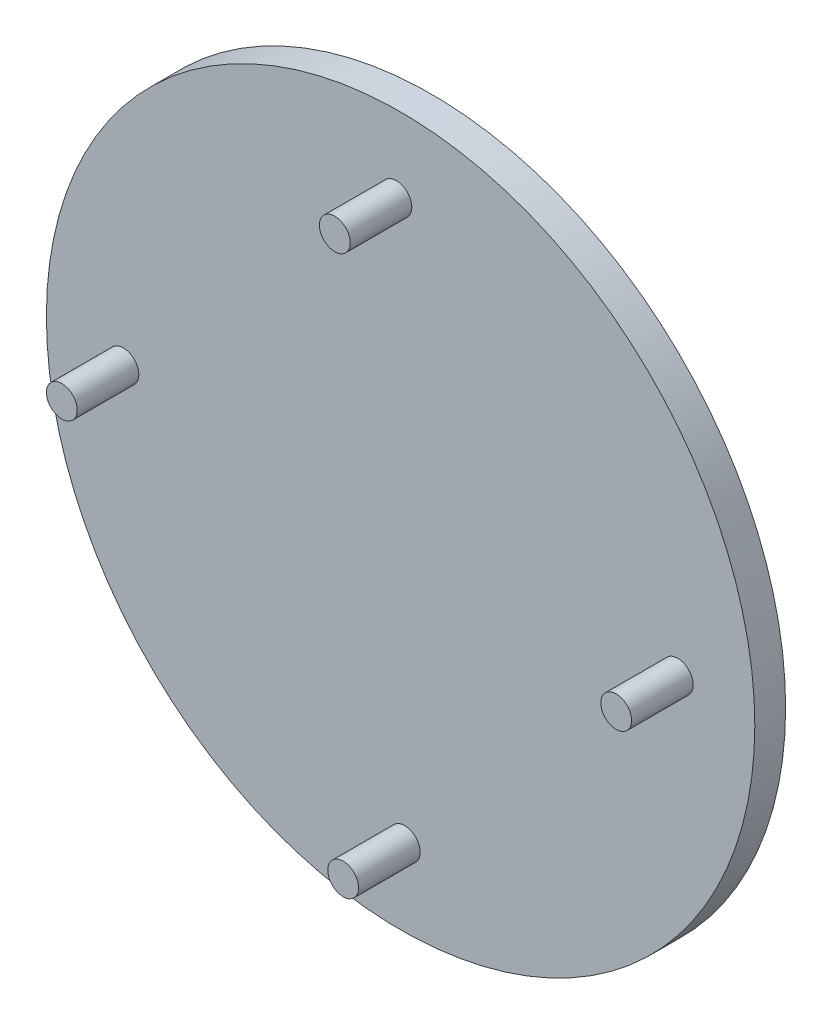
SolidWorks part; units mm, degrees
ref_plane "Front Plane" through (0, 0, 0) normal (0, 0, 1) x (1, 0, 0)
ref_plane "Top Plane" through (0, 0, 0) normal (0, 1, 0) x (1, 0, 0)
ref_plane "Right Plane" through (0, 0, 0) normal (1, 0, 0) x (0, 0, -1)
sketch "Sketch1" plane through (0, 0, 0) normal (0, 0, 1) x (1, 0, 0)
  circle A0 centre (0, -0.2533) radius 11.5
  dimension "D1" = 23
extrude "Boss-Extrude1" add sketch "Sketch1" against normal blind 1
sketch "Sketch4" plane through (0, 0, 0) normal (0, 0, 1) x (1, 0, 0)
  line L0 (-9, 0) -> (13.027, 0) construction
  circle A0 centre (0, 0) radius 9 construction
  circle A1 centre (8.9992, -0.1173) radius 0.5
  dimension "D1" = 1
extrude "Boss-Extrude4" add sketch "Sketch4" along normal blind 2
pattern_circular "CirPattern3" count 4 over 360 about axis through (0, -0.2533, 0) along (0, 0, 1) of "Boss-Extrude4"
